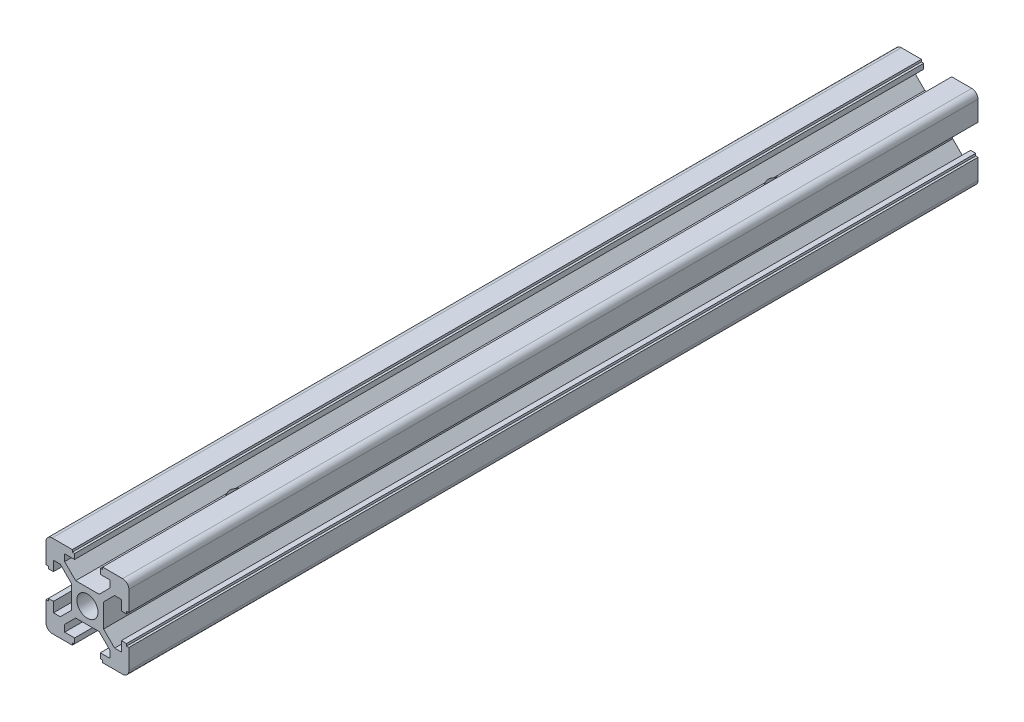
SolidWorks part; units mm, degrees
material "6063-T5"
ref_plane "前视基准面" through (0, 0, 0) normal (0, 0, 1) x (1, 0, 0)
ref_plane "上视基准面" through (0, 0, 0) normal (0, 1, 0) x (1, 0, 0)
ref_plane "右视基准面" through (0, 0, 0) normal (1, 0, 0) x (0, 0, -1)
sketch "草图2" plane through (0, 0, 0) normal (0, 0, 1) x (1, 0, 0)
  line L0 (-3.9, 2.8393) -> (-6.5607, 5.5)
  line L1 (-2.8393, 3.9) -> (2.8393, 3.9)
  line L2 (-3.9, 2.8393) -> (-3.9, -2.8393)
  line L3 (-2.8393, -3.9) -> (2.8393, -3.9)
  line L4 (3.9, 2.8393) -> (3.9, -2.8393)
  line L5 (-3.9, 3.9) -> (3.9, -3.9) construction
  line L6 (-3.9, -3.9) -> (3.9, 3.9) construction
  line L7 (-2.8393, 3.9) -> (-5.5, 6.5607)
  line L8 (-5.5, 6.5607) -> (-5.5, 8.2)
  line L9 (-5.5, 8.2) -> (-3.1, 8.2)
  line L10 (-3.1, 8.2) -> (-3.1, 9.45)
  line L11 (-3.1, 9.45) -> (-3.65, 9.45)
  line L12 (-3.65, 9.45) -> (-3.65, 10)
  line L13 (-3.65, 10) -> (-8.5, 10)
  line L14 (-6.5607, 5.5) -> (-8.2, 5.5)
  line L15 (-10, 3.65) -> (-10, 8.5)
  line L16 (-9.45, 3.65) -> (-10, 3.65)
  line L17 (-9.45, 3.1) -> (-9.45, 3.65)
  line L18 (-8.2, 3.1) -> (-9.45, 3.1)
  line L19 (-8.2, 5.5) -> (-8.2, 3.1)
  line L20 (2.8393, 3.9) -> (5.5, 6.5607)
  line L21 (3.9, 2.8393) -> (6.5607, 5.5)
  line L22 (6.5607, 5.5) -> (8.2, 5.5)
  line L23 (8.2, 5.5) -> (8.2, 3.1)
  line L24 (8.2, 3.1) -> (9.45, 3.1)
  line L25 (9.45, 3.1) -> (9.45, 3.65)
  line L26 (9.45, 3.65) -> (10, 3.65)
  line L27 (10, 3.65) -> (10, 8.5)
  line L28 (5.5, 6.5607) -> (5.5, 8.2)
  line L29 (3.65, 10) -> (8.5, 10)
  line L30 (3.65, 9.45) -> (3.65, 10)
  line L31 (3.1, 9.45) -> (3.65, 9.45)
  line L32 (3.1, 8.2) -> (3.1, 9.45)
  line L33 (5.5, 8.2) -> (3.1, 8.2)
  line L34 (3.9, -2.8393) -> (6.5607, -5.5)
  line L35 (2.8393, -3.9) -> (5.5, -6.5607)
  line L36 (5.5, -6.5607) -> (5.5, -8.2)
  line L37 (5.5, -8.2) -> (3.1, -8.2)
  line L38 (3.1, -8.2) -> (3.1, -9.45)
  line L39 (3.1, -9.45) -> (3.65, -9.45)
  line L40 (3.65, -9.45) -> (3.65, -10)
  line L41 (3.65, -10) -> (8.5, -10)
  line L42 (6.5607, -5.5) -> (8.2, -5.5)
  line L43 (10, -3.65) -> (10, -8.5)
  line L44 (9.45, -3.65) -> (10, -3.65)
  line L45 (9.45, -3.1) -> (9.45, -3.65)
  line L46 (8.2, -3.1) -> (9.45, -3.1)
  line L47 (8.2, -5.5) -> (8.2, -3.1)
  line L48 (-2.8393, -3.9) -> (-5.5, -6.5607)
  line L49 (-3.9, -2.8393) -> (-6.5607, -5.5)
  line L50 (-6.5607, -5.5) -> (-8.2, -5.5)
  line L51 (-8.2, -5.5) -> (-8.2, -3.1)
  line L52 (-8.2, -3.1) -> (-9.45, -3.1)
  line L53 (-9.45, -3.1) -> (-9.45, -3.65)
  line L54 (-9.45, -3.65) -> (-10, -3.65)
  line L55 (-10, -3.65) -> (-10, -8.5)
  line L56 (-5.5, -6.5607) -> (-5.5, -8.2)
  line L57 (-3.65, -10) -> (-8.5, -10)
  line L58 (-3.65, -9.45) -> (-3.65, -10)
  line L59 (-3.1, -9.45) -> (-3.65, -9.45)
  line L60 (-3.1, -8.2) -> (-3.1, -9.45)
  line L61 (-5.5, -8.2) -> (-3.1, -8.2)
  circle A0 centre (0, 0) radius 2.55
  arc A1 (-8.5, 10) -> (-10, 8.5) centre (-8.5, 8.5) ccw
  arc A2 (10, 8.5) -> (8.5, 10) centre (8.5, 8.5) ccw
  arc A3 (8.5, -10) -> (10, -8.5) centre (8.5, -8.5) ccw
  arc A4 (-10, -8.5) -> (-8.5, -10) centre (-8.5, -8.5) ccw
  point P25 (-10, 10)
  point P79 (0, 0)
  dimension "D1" = 5.1
  dimension "D9" = 1.5
  dimension "D2" = 7.8
  dimension "D3" = 1.5
  dimension "D4" = 10
  dimension "D5" = 3.1
  dimension "D6" = 0.55
  dimension "D7" = 1.8
  dimension "D8" = 5.5
  dimension "D11" = 3.9
  dimension "D10" = 4
extrude "凸台-拉伸1" add sketch "草图2" along normal blind 205
sketch "草图3" plane through (0, -10, 0) normal (0, -1, 0) x (1, 0, 0)
  line L0 (0, 205) -> (0, 0) construction
  line L1 (-2.8393, 205) -> (2.8393, 205) construction
  circle A0 centre (0, 167.5) radius 3
  circle A1 centre (0, 37.5) radius 3
  point P9 (10.5001, 37.5)
  point P10 (0, 102.5)
  dimension "D2" = 6
  dimension "D3" = 6
  dimension "D1" = 130
  dimension "D4" = 65
  dimension "D5" = 65
extrude "切除-拉伸1" cut sketch "草图3" against normal through all
